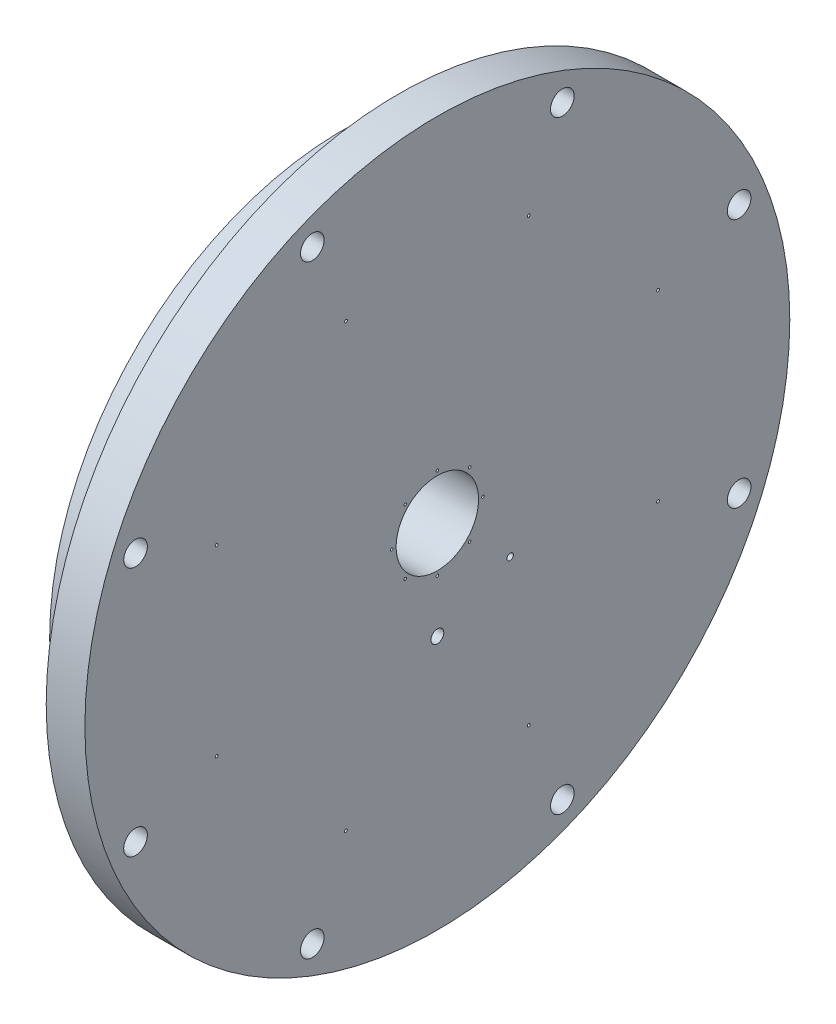
SolidWorks part; units mm, degrees
ref_plane "Front Plane" through (0, 0, 0) normal (0, 0, 1) x (1, 0, 0)
ref_plane "Top Plane" through (0, 0, 0) normal (0, 1, 0) x (1, 0, 0)
ref_plane "Right Plane" through (0, 0, 0) normal (1, 0, 0) x (0, 0, -1)
sketch "Body Sketch" plane through (0, 0, 0) normal (0, 0, 1) x (1, 0, 0)
  line L0 (-60, 0) -> (20, 0) construction
  line L1 (0, 9.5949) -> (0, 82)
  line L2 (0, 82) -> (-9, 82)
  line L3 (-9, 82) -> (-9, 68.2)
  line L4 (-9, 68.2) -> (-22, 68.2)
  line L5 (-22, 68.2) -> (-22, 9.5949)
  line L6 (-22, 9.5949) -> (0, 9.5949)
revolve "Body" add sketch "Body Sketch" angle 360 about L0
ref_axis "Engine Axis" through (1.1, 0, 0) along (-1, 0, 0)
sketch "Fuel Ring Sketch" plane through (0, 0, 0) normal (0, 0, 1) x (1, 0, 0)
  line L0 (-60, 0) -> (20, 0) construction
  line L1 (-8.3, 58.65) -> (-1.6, 58.65)
  line L2 (-1.6, 58.65) -> (-1.6, 61.15)
  line L3 (-1.6, 61.15) -> (-8.3, 61.15)
  line L4 (-8.3, 61.15) -> (-8.3, 58.65)
revolve "Fuel Ring" cut sketch "Fuel Ring Sketch" angle 360 about L0
sketch "Core Manifold Sketch" plane through (0, 0, 0) normal (0, 0, 1) x (1, 0, 0)
  line L0 (-60, 0) -> (20, 0) construction
  line L1 (-8.3, 10.1949) -> (-1.6, 10.1949)
  line L2 (-1.6, 10.1949) -> (-1.6, 11.7949)
  line L3 (-1.6, 11.7949) -> (-8.3, 11.7949)
  line L4 (-8.3, 11.7949) -> (-8.3, 10.1949)
revolve "Core Manifold" cut sketch "Core Manifold Sketch" angle 360 about L0
sketch "Film Manifold Sketch" plane through (0, 0, 0) normal (0, 0, 1) x (1, 0, 0)
  line L0 (-60, 0) -> (20, 0) construction
  line L1 (-4.4, 54.8192) -> (-1.6, 54.8192)
  line L2 (-1.6, 54.8192) -> (-1.6, 56.3192)
  line L3 (-1.6, 56.3192) -> (-4.4, 56.3192)
  line L4 (-4.4, 56.3192) -> (-4.4, 54.8192)
revolve "Film Manifold" cut sketch "Film Manifold Sketch" angle 360 about L0
sketch "Pintle Seal Groove Sketch" plane through (0, 0, 0) normal (0, 0, 1) x (1, 0, 0)
  line L0 (-60, 0) -> (20, 0) construction
  line L1 (-22, 11.2) -> (-20.7, 11.2)
  line L2 (-20.7, 11.2) -> (-20.7, 13.6)
  line L3 (-20.7, 13.6) -> (-22, 13.6)
  line L4 (-22, 13.6) -> (-22, 11.2)
revolve "Pintle Seal Groove" cut sketch "Pintle Seal Groove Sketch" angle 360 about L0
sketch "Feed Passage Sketch" plane through (0, 0, 0) normal (0, 0, 1) x (1, 0, 0)
  line L0 (-6.8, 0) -> (-6.8, 60) construction
  line L1 (-6.8, 10.9949) -> (-5.3, 10.9949)
  line L2 (-5.3, 10.9949) -> (-5.3, 59.9)
  line L3 (-5.3, 59.9) -> (-6.8, 59.9)
  line L4 (-6.8, 59.9) -> (-6.8, 10.9949)
revolve "Feed Passage" cut sketch "Feed Passage Sketch" angle 360 about L0
pattern_circular "Feed Passages x3" count 3 over 360 about axis through (1.1, 0, 0) along (-1, 0, 0) of "Feed Passage"
sketch "Ethanol Hole Sketch" plane through (0, 0, 0) normal (1, 0, 0) x (0, 0, -1)
  circle A0 centre (0, 10.5987) radius 0.3038
extrude "Ethanol Hole" cut sketch "Ethanol Hole Sketch" against normal blind 1.8
pattern_circular "Ethanol Holes x8" count 8 over 360 about axis through (0, 0, 0) along (1, 0, 0) of "Ethanol Hole"
sketch "Film Hole Sketch" plane through (0, 0, 0) normal (1, 0, 0) x (0, 0, -1)
  circle A0 centre (21.2654, 51.3392) radius 0.3334
extrude "Film Hole" cut sketch "Film Hole Sketch" against normal blind 1.8
pattern_circular "Film Holes x8" count 8 over 360 about axis through (0, 0, 0) along (1, 0, 0) of "Film Hole"
sketch "Bolt Hole Sketch" plane through (0, 0, 0) normal (1, 0, 0) x (0, 0, -1)
  circle A0 centre (29.0839, 70.2148) radius 2.75
extrude "Bolt Hole" cut sketch "Bolt Hole Sketch" against normal blind 9
pattern_circular "Bolt Holes x8" count 8 over 360 about axis through (0, 0, 0) along (1, 0, 0) of "Bolt Hole"
ref_plane "Back Face Plane" through (-22, 0, 0) normal (1, 0, 0) x (0, 0, -1)
sketch "Igniter Port (-4 ORB) Sketch" plane through (-22, 0, 0) normal (1, 0, 0) x (0, 0, -1)
  circle A0 centre (0, -22.8) radius 4.953
extrude "Igniter Port (-4 ORB)" cut sketch "Igniter Port (-4 ORB) Sketch" along normal blind 10.5
sketch "Igniter Passage Sketch" plane through (-22, 0, 0) normal (1, 0, 0) x (0, 0, -1)
  circle A0 centre (0, -22.8) radius 1.5
extrude "Igniter Passage" cut sketch "Igniter Passage Sketch" along normal blind 22.5
sketch "Pc Tap Port (-4 ORB) Sketch" plane through (-22, 0, 0) normal (1, 0, 0) x (0, 0, -1)
  circle A0 centre (16.9437, -15.2562) radius 4.953
extrude "Pc Tap Port (-4 ORB)" cut sketch "Pc Tap Port (-4 ORB) Sketch" along normal blind 10.5
sketch "Pc Tap Passage Sketch" plane through (-22, 0, 0) normal (1, 0, 0) x (0, 0, -1)
  circle A0 centre (16.9437, -15.2562) radius 0.75
extrude "Pc Tap Passage" cut sketch "Pc Tap Passage Sketch" along normal blind 22.5
sketch "Ethanol Inlet Port (-4 ORB) Sketch" plane through (-22, 0, 0) normal (1, 0, 0) x (0, 0, -1)
  circle A0 centre (0, 55.5692) radius 4.953
extrude "Ethanol Inlet Port (-4 ORB)" cut sketch "Ethanol Inlet Port (-4 ORB) Sketch" along normal blind 10.5
sketch "Ethanol Inlet Passage Sketch" plane through (-22, 0, 0) normal (1, 0, 0) x (0, 0, -1)
  circle A0 centre (0, 55.5692) radius 2
extrude "Ethanol Inlet Passage" cut sketch "Ethanol Inlet Passage Sketch" along normal blind 15.2
sketch "Film Restrictor Sketch" plane through (-22, 0, 0) normal (1, 0, 0) x (0, 0, -1)
  circle A0 centre (0, 55.5692) radius 0.4345
extrude "Film Restrictor" cut sketch "Film Restrictor Sketch" along normal blind 18.16
sketch "Pintle Bolt Tap Drill (M4) Sketch" plane through (-22, 0, 0) normal (1, 0, 0) x (0, 0, -1)
  circle A0 centre (19, 0) radius 1.65
extrude "Pintle Bolt Tap Drill (M4)" cut sketch "Pintle Bolt Tap Drill (M4) Sketch" along normal blind 10
pattern_circular "Pintle Bolt Holes x2" count 2 over 360 about axis through (0, 0, 0) along (1, 0, 0) of "Pintle Bolt Tap Drill (M4)"
sketch "Torch Ethanol Port Sketch" plane through (-22, 0, 0) normal (1, 0, 0) x (0, 0, -1)
  circle A0 centre (-22.5167, -13) radius 3.5
extrude "Torch Ethanol Port" cut sketch "Torch Ethanol Port Sketch" along normal blind 8.6
sketch "Torch Ethanol Drilling Sketch" plane through (-22, 0, 0) normal (1, 0, 0) x (0, 0, -1)
  circle A0 centre (-22.5167, -13) radius 1
extrude "Torch Ethanol Drilling" cut sketch "Torch Ethanol Drilling Sketch" along normal blind 15.2
